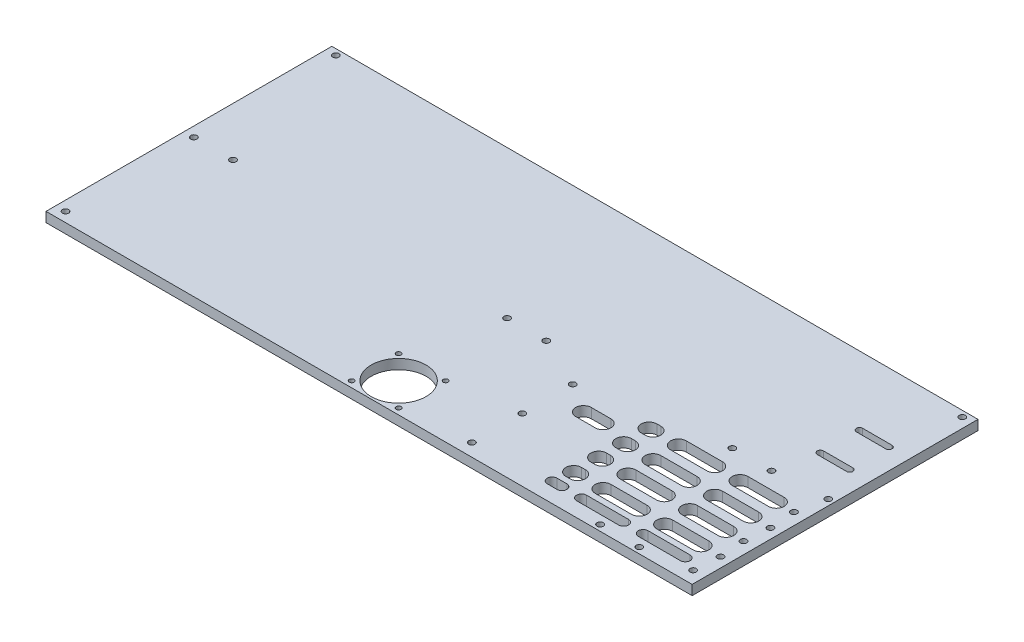
SolidWorks part; units mm, degrees
ref_plane "前视基准面" through (0, 0, 0) normal (0, 0, 1) x (1, 0, 0)
ref_plane "上视基准面" through (0, 0, 0) normal (0, 1, 0) x (1, 0, 0)
ref_plane "右视基准面" through (0, 0, 0) normal (1, 0, 0) x (0, 0, -1)
sketch "草图1" plane through (0, 0, 0) normal (0, 1, 0) x (1, 0, 0)
  line L1 (0, 0) -> (330, 0)
  line L2 (0, 0) -> (0, 146)
  line L3 (0, 146) -> (330, 146)
  line L4 (330, 0) -> (330, 146)
  dimension "D1" = 146
  dimension "D2" = 330
extrude "凸台-拉伸1" add sketch "草图1" along normal blind 5
sketch "草图2" plane through (0, 5, 0) normal (0, 1, 0) x (1, 0, 0)
  line L0 (5, 70.5) -> (25, 70.5) construction
  line L1 (165, 70.5) -> (185, 70.5) construction
  line L2 (0, 146) -> (0, 0) construction
  line L3 (0, 0) -> (330, 0) construction
  line L4 (35, 3) -> (55, 3) construction
  line L5 (280, 3) -> (300, 3) construction
  line L6 (330, 0) -> (330, 146) construction
  line L7 (312, 91) -> (312, 111) construction
  line L8 (330, 146) -> (0, 146) construction
  line L9 (304.5, 111) -> (319.5, 111) construction
  line L10 (304.5, 112.6) -> (319.5, 112.6)
  line L11 (304.5, 109.4) -> (319.5, 109.4)
  line L12 (304.5, 91) -> (319.5, 91) construction
  line L13 (304.5, 92.6) -> (319.5, 92.6)
  line L14 (304.5, 89.4) -> (319.5, 89.4)
  line L15 (280, 70.5) -> (300, 70.5) construction
  circle A0 centre (5, 70.5) radius 1.6
  circle A1 centre (25, 70.5) radius 1.6
  circle A2 centre (165, 70.5) radius 1.6
  circle A3 centre (185, 70.5) radius 1.6
  circle A4 centre (35, 3) radius 1.6 construction
  circle A5 centre (55, 3) radius 1.6 construction
  circle A6 centre (280, 3) radius 1.6
  circle A7 centre (300, 3) radius 1.6
  circle A8 centre (312, 91) radius 1.6 construction
  circle A9 centre (312, 111) radius 1.6 construction
  arc A10 (304.5, 112.6) -> (304.5, 109.4) centre (304.5, 111) ccw
  arc A11 (319.5, 109.4) -> (319.5, 112.6) centre (319.5, 111) ccw
  arc A12 (304.5, 92.6) -> (304.5, 89.4) centre (304.5, 91) ccw
  arc A13 (319.5, 89.4) -> (319.5, 92.6) centre (319.5, 91) ccw
  circle A14 centre (280, 70.5) radius 1.6
  circle A15 centre (300, 70.5) radius 1.6
  point P30 (312, 111)
  point P36 (312, 91)
  dimension "D5" = 3.2
  dimension "D9" = 35
  dimension "D10" = 18
  dimension "D1" = 20
  dimension "D2" = 5
  dimension "D3" = 165
  dimension "D4" = 70.5
  dimension "D6" = 3
  dimension "D7" = 35
  dimension "D8" = 30
  dimension "D11" = 15
  dimension "D12" = 30
extrude "切除-拉伸1" cut sketch "草图2" against normal through all
sketch "草图3" plane through (0, 5, 0) normal (0, 1, 0) x (1, 0, 0)
  line L0 (211, 32.25) -> (324, 32.25) construction
  line L1 (211, 6.5) -> (324, 6.5) construction
  line L2 (211, 6.5) -> (211, 58) construction
  line L3 (211, 58) -> (324, 58) construction
  line L4 (324, 6.5) -> (324, 58) construction
  line L5 (0, 0) -> (330, 0) construction
  line L6 (330, 0) -> (330, 146) construction
  circle A0 centre (211, 58) radius 1.6
  circle A1 centre (324, 58) radius 1.6
  circle A2 centre (324, 32.25) radius 1.6
  circle A3 centre (211, 32.25) radius 1.6
  circle A4 centre (211, 6.5) radius 1.6
  circle A5 centre (324, 6.5) radius 1.6
  dimension "D3" = 3.2
  dimension "D1" = 51.5
  dimension "D2" = 113
  dimension "D4" = 6.5
  dimension "D5" = 6
extrude "切除-拉伸2" cut sketch "草图3" against normal through all
sketch "草图5" plane through (0, 5, 0) normal (0, 1, 0) x (1, 0, 0)
  line L0 (330, 0) -> (330, 146) construction
  line L1 (324, 58) -> (324, 32.25) construction
  line L2 (324, 32.25) -> (324, 6.5) construction
  line L5 (330, 146) -> (0, 146) construction
  line L6 (0, 146) -> (0, 0) construction
  line L7 (0, 0) -> (330, 0) construction
  circle A0 centre (325, 19.5) radius 1.6
  circle A1 centre (325, 45) radius 1.6
  circle A2 centre (327, 72.5) radius 1.6
  circle A3 centre (324, 58) radius 1.6 construction
  circle A4 centre (300, 70.5) radius 1.6 construction
  circle A5 centre (325, 143) radius 1.6
  circle A6 centre (5, 143) radius 1.6
  circle A7 centre (5, 5) radius 1.6
  dimension "D1" = 5
  dimension "D2" = 2
  dimension "D3" = 3
  dimension "D4" = 3
  dimension "D5" = 5
  dimension "D6" = 5
  dimension "D7" = 5
  dimension "D8" = 3
  dimension "D9" = 5
  dimension "D10" = 19.5
  dimension "D11" = 45
extrude "切除-拉伸3" cut sketch "草图5" against normal up to next
sketch "草图6" plane through (0, 5, 0) normal (0, 1, 0) x (1, 0, 0)
  line L0 (330, 0) -> (330, 146) construction
  line L1 (250, 10) -> (315, 10) construction
  line L2 (250, 10) -> (250, 60) construction
  line L3 (250, 60) -> (315, 60) construction
  line L4 (315, 10) -> (315, 60) construction
  line L5 (0, 0) -> (330, 0) construction
  line L6 (296.5, 58) -> (315, 58) construction
  line L7 (296.5, 62) -> (315, 62)
  line L8 (296.5, 54) -> (315, 54)
  line L9 (315, 45) -> (296.5, 45) construction
  line L10 (315, 41) -> (296.5, 41)
  line L11 (315, 49) -> (296.5, 49)
  line L12 (296.5, 32.25) -> (315, 32.25) construction
  line L13 (296.5, 36.25) -> (315, 36.25)
  line L14 (296.5, 28.25) -> (315, 28.25)
  line L15 (296.5, 19.5) -> (315, 19.5) construction
  line L16 (296.5, 23.5) -> (315, 23.5)
  line L17 (296.5, 15.5) -> (315, 15.5)
  line L18 (324, 58) -> (315, 58) construction
  line L19 (280, 70.5) -> (300, 70.5) construction
  line L20 (325, 45) -> (315, 45) construction
  line L21 (290, 70.5) -> (290, 10) construction
  line L22 (324, 32.25) -> (315, 32.25) construction
  line L23 (283.5, 19.5) -> (265, 19.5) construction
  line L24 (325, 19.5) -> (315, 19.5) construction
  line L25 (283.5, 23.5) -> (265, 23.5)
  line L26 (283.5, 15.5) -> (265, 15.5)
  line L27 (283.5, 32.25) -> (265, 32.25) construction
  line L28 (283.5, 36.25) -> (265, 36.25)
  line L29 (283.5, 28.25) -> (265, 28.25)
  line L30 (265, 45) -> (283.5, 45) construction
  line L31 (265, 41) -> (283.5, 41)
  line L32 (265, 49) -> (283.5, 49)
  line L33 (283.5, 58) -> (265, 58) construction
  line L34 (283.5, 62) -> (265, 62)
  line L35 (283.5, 54) -> (265, 54)
  line L36 (295, 10) -> (316.5, 10) construction
  line L39 (295, 12.5) -> (316.5, 12.5)
  line L40 (295, 7.5) -> (316.5, 7.5)
  line L41 (285, 10) -> (263.5, 10) construction
  line L42 (285, 12.5) -> (263.5, 12.5)
  line L43 (285, 7.5) -> (263.5, 7.5)
  line L44 (250, 58) -> (252, 58) construction
  line L45 (250, 62) -> (252, 62)
  line L46 (250, 54) -> (252, 54)
  line L47 (250, 45) -> (252, 45) construction
  line L48 (250, 49) -> (252, 49)
  line L49 (250, 41) -> (252, 41)
  line L50 (250, 32.25) -> (252, 32.25) construction
  line L51 (250, 36.25) -> (252, 36.25)
  line L52 (250, 28.25) -> (252, 28.25)
  line L53 (250, 19.5) -> (252, 19.5) construction
  line L54 (250, 23.5) -> (252, 23.5)
  line L55 (250, 15.5) -> (252, 15.5)
  line L56 (248.5, 10) -> (253.5, 10) construction
  line L59 (248.5, 12.5) -> (253.5, 12.5)
  line L60 (248.5, 7.5) -> (253.5, 7.5)
  line L61 (226, 48.5) -> (236, 48.5) construction
  line L62 (226, 52.5) -> (236, 52.5)
  line L63 (226, 44.5) -> (236, 44.5)
  line L64 (330, 0) -> (330, 146) construction
  line L65 (0, 0) -> (330, 0) construction
  arc A0 (296.5, 62) -> (296.5, 54) centre (296.5, 58) ccw
  arc A1 (315, 54) -> (315, 62) centre (315, 58) ccw
  arc A2 (315, 41) -> (315, 49) centre (315, 45) ccw
  arc A3 (296.5, 49) -> (296.5, 41) centre (296.5, 45) ccw
  arc A4 (296.5, 36.25) -> (296.5, 28.25) centre (296.5, 32.25) ccw
  arc A5 (315, 28.25) -> (315, 36.25) centre (315, 32.25) ccw
  arc A6 (296.5, 23.5) -> (296.5, 15.5) centre (296.5, 19.5) ccw
  arc A7 (315, 15.5) -> (315, 23.5) centre (315, 19.5) ccw
  arc A8 (283.5, 23.5) -> (283.5, 15.5) centre (283.5, 19.5) cw
  arc A9 (265, 15.5) -> (265, 23.5) centre (265, 19.5) cw
  arc A10 (283.5, 36.25) -> (283.5, 28.25) centre (283.5, 32.25) cw
  arc A11 (265, 28.25) -> (265, 36.25) centre (265, 32.25) cw
  arc A12 (265, 41) -> (265, 49) centre (265, 45) cw
  arc A13 (283.5, 49) -> (283.5, 41) centre (283.5, 45) cw
  arc A14 (283.5, 62) -> (283.5, 54) centre (283.5, 58) cw
  arc A15 (265, 54) -> (265, 62) centre (265, 58) cw
  arc A18 (295, 12.5) -> (295, 7.5) centre (295, 10) ccw
  arc A19 (316.5, 7.5) -> (316.5, 12.5) centre (316.5, 10) ccw
  arc A20 (285, 12.5) -> (285, 7.5) centre (285, 10) cw
  arc A21 (263.5, 7.5) -> (263.5, 12.5) centre (263.5, 10) cw
  arc A22 (250, 62) -> (250, 54) centre (250, 58) ccw
  arc A23 (252, 54) -> (252, 62) centre (252, 58) ccw
  arc A24 (250, 49) -> (250, 41) centre (250, 45) ccw
  arc A25 (252, 41) -> (252, 49) centre (252, 45) ccw
  arc A26 (250, 36.25) -> (250, 28.25) centre (250, 32.25) ccw
  arc A27 (252, 28.25) -> (252, 36.25) centre (252, 32.25) ccw
  arc A28 (250, 23.5) -> (250, 15.5) centre (250, 19.5) ccw
  arc A29 (252, 15.5) -> (252, 23.5) centre (252, 19.5) ccw
  arc A32 (248.5, 12.5) -> (248.5, 7.5) centre (248.5, 10) ccw
  arc A33 (253.5, 7.5) -> (253.5, 12.5) centre (253.5, 10) ccw
  arc A34 (226, 52.5) -> (226, 44.5) centre (226, 48.5) ccw
  arc A35 (236, 44.5) -> (236, 52.5) centre (236, 48.5) ccw
  point P10 (305.75, 58)
  point P15 (305.75, 45)
  point P22 (305.75, 32.25)
  point P29 (305.75, 19.5)
  point P51 (292.5, 19.5)
  point P58 (274.25, 19.5)
  point P65 (274.25, 32.25)
  point P72 (274.25, 45)
  point P79 (274.25, 58)
  point P85 (305.75, 10)
  point P90 (292.5, 10)
  point P91 (319, 19.5)
  point P92 (319, 10)
  point P95 (274.25, 10)
  point P102 (251, 58)
  point P107 (251, 45)
  point P114 (251, 32.25)
  point P121 (251, 19.5)
  point P130 (251, 10)
  point P135 (256, 58)
  point P136 (261, 58)
  point P138 (256, 10)
  point P139 (256, 19.5)
  point P140 (246, 19.5)
  point P141 (246, 10)
  point P143 (231, 48.5)
  dimension "D1" = 15
  dimension "D2" = 10
  dimension "D3" = 50
  dimension "D4" = 65
  dimension "D5" = 8
  dimension "D6" = 5
  dimension "D7" = 3
  dimension "D8" = 5
  dimension "D9" = 8
  dimension "D10" = 10
  dimension "D11" = 94
  dimension "D12" = 48.5
extrude "切除-拉伸4" cut sketch "草图6" against normal up to next
sketch "草图7" plane through (0, 5, 0) normal (0, 1, 0) x (1, 0, 0)
  line L0 (0, 0) -> (330, 0) construction
  line L1 (153, 3.1) -> (177, 3.1) construction
  line L2 (153, 3.1) -> (153, 27.1) construction
  line L3 (153, 27.1) -> (177, 27.1) construction
  line L4 (177, 3.1) -> (177, 27.1) construction
  line L5 (153, 3.1) -> (177, 27.1) construction
  line L6 (153, 27.1) -> (177, 3.1) construction
  circle A0 centre (165, 15.1) radius 14
  circle A1 centre (153, 27.1) radius 1.25
  circle A2 centre (177, 27.1) radius 1.25
  circle A3 centre (177, 3.1) radius 1.25
  circle A4 centre (153, 3.1) radius 1.25
  dimension "D1" = 28
  dimension "D3" = 2.5
  dimension "D2" = 24
  dimension "D4" = 15.1
  dimension "D5" = 165
extrude "切除-拉伸5" cut sketch "草图7" against normal blind 10
